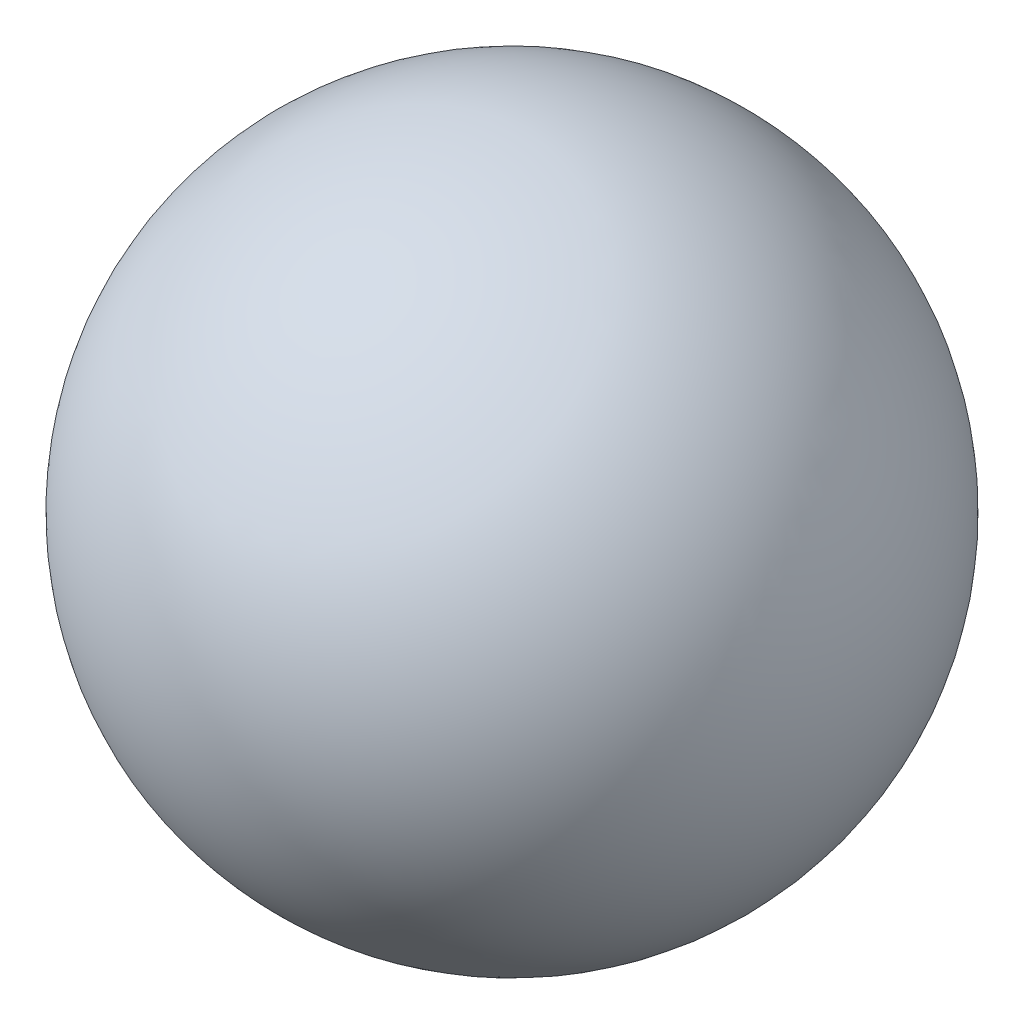
SolidWorks part; units mm, degrees
ref_plane "Front Plane" through (0, 0, 0) normal (0, 0, 1) x (1, 0, 0)
ref_plane "Top Plane" through (0, 0, 0) normal (0, 1, 0) x (1, 0, 0)
ref_plane "Right Plane" through (0, 0, 0) normal (1, 0, 0) x (0, 0, -1)
ref_plane "Plane1" through (0, 0, 0) normal (0, 0, -1) x (-1, 0, 0)
sketch "Sketch1" plane through (0, 0, 0) normal (0, 0, -1) x (-1, 0, 0)
  line L0 (-1.605, 2.7799) -> (-2.3638, 4.0941)
  line L1 (-1.561, 2.7037) -> (-2.4586, 4.2584) construction
  arc A0 (-2.3638, 4.0941) -> (-1.605, 2.7799) centre (-1.9844, 3.437) ccw
revolve "Revolve1" add sketch "Sketch1" angle 360 about L1
